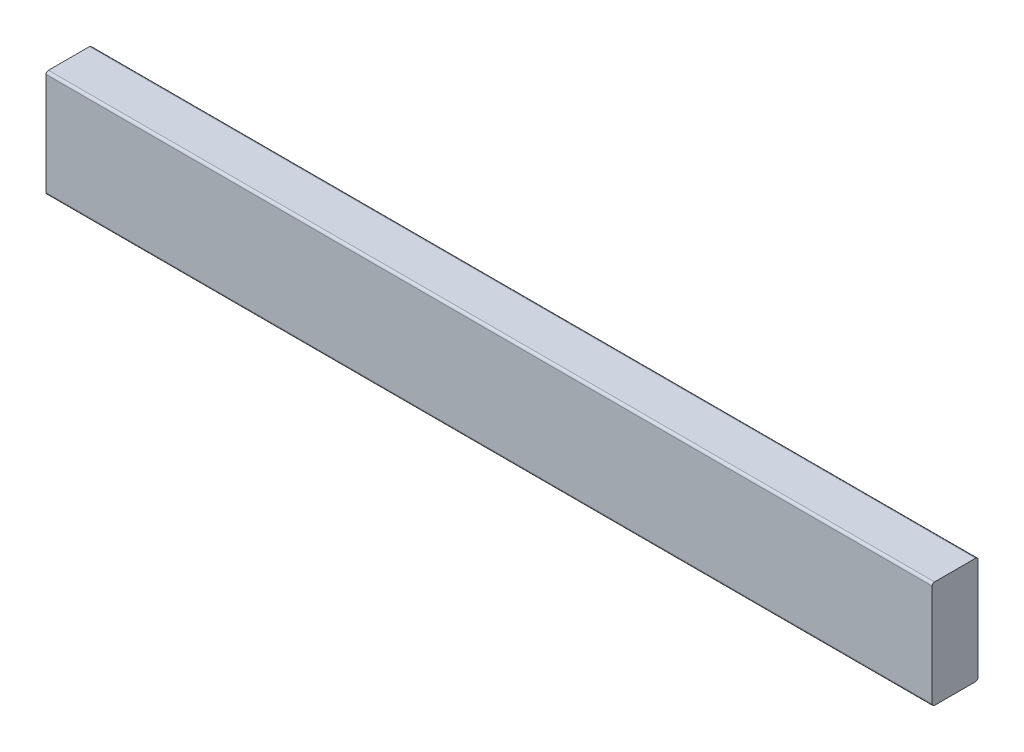
SolidWorks part; units mm, degrees
ref_plane "Front Plane" through (0, 0, 0) normal (0, 0, 1) x (1, 0, 0)
ref_plane "Top Plane" through (0, 0, 0) normal (0, 1, 0) x (1, 0, 0)
ref_plane "Right Plane" through (0, 0, 0) normal (1, 0, 0) x (0, 0, -1)
sketch "Sketch1" plane through (0, 0, 0) normal (1, 0, 0) x (0, -1, 0)
  line L1 (-44.45, -19.05) -> (44.45, -19.05)
  line L2 (-44.45, -19.05) -> (-44.45, 19.05)
  line L3 (-44.45, 19.05) -> (44.45, 19.05)
  line L4 (44.45, -19.05) -> (44.45, 19.05)
  line L5 (-44.45, -19.05) -> (44.45, 19.05) construction
  line L6 (-44.45, 19.05) -> (44.45, -19.05) construction
  point P0 (0, 0)
  dimension "D1" = 38.1
  dimension "D2" = 88.9
extrude "Boss-Extrude1" add sketch "Sketch1" along normal blind 736.6
fillet "Fillet1" radius 2 4 edges at (368.3, 44.45, -19.05) (368.3, -44.45, -19.05) (368.3, -44.45, 19.05) (368.3, 44.45, 19.05)
